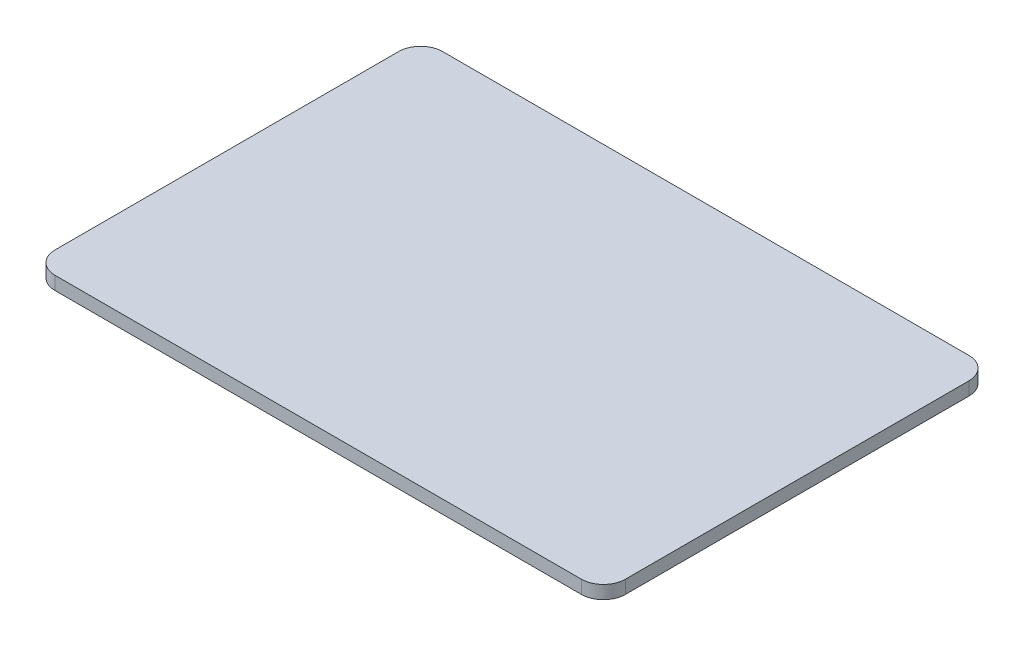
SolidWorks part; units mm, degrees
ref_plane "Front Plane" through (0, 0, 0) normal (0, 0, 1) x (1, 0, 0)
ref_plane "Top Plane" through (0, 0, 0) normal (0, 1, 0) x (1, 0, 0)
ref_plane "Right Plane" through (0, 0, 0) normal (1, 0, 0) x (0, 0, -1)
sketch "Sketch1" plane through (0, 0, 0) normal (0, 1, 0) x (1, 0, 0)
  line L1 (-129.5, 88) -> (129.5, 88)
  line L2 (-129.5, 88) -> (-129.5, -88)
  line L3 (-129.5, -88) -> (129.5, -88)
  line L4 (129.5, 88) -> (129.5, -88)
  line L5 (-129.5, 88) -> (129.5, -88) construction
  line L6 (-129.5, -88) -> (129.5, 88) construction
  point P0 (0, 0)
  dimension "D1" = 259
  dimension "D2" = 176
extrude "Boss-Extrude1" add sketch "Sketch1" along normal blind 6
fillet "Fillet1" radius 10 4 edges at (-129.5, 3, -88) (-129.5, 3, 88) (129.5, 3, -88) (129.5, 3, 88)
